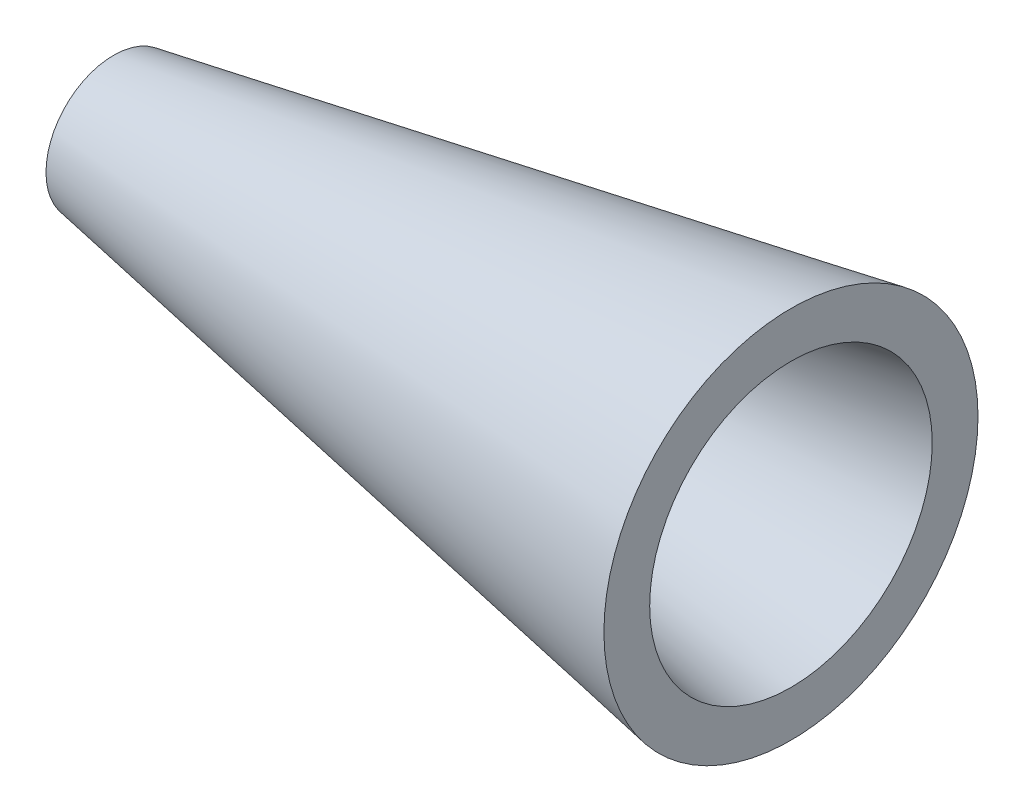
SolidWorks part; units mm, degrees
ref_plane "Front Plane" through (0, 0, 0) normal (0, 0, 1) x (1, 0, 0)
ref_plane "Top Plane" through (0, 0, 0) normal (0, 1, 0) x (1, 0, 0)
ref_plane "Right Plane" through (0, 0, 0) normal (1, 0, 0) x (0, 0, -1)
sketch "Sketch1" plane through (0, 0, 0) normal (0, 0, 1) x (1, 0, 0)
  line L0 (-20.9326, 0) -> (26.7602, 0) construction
  line L1 (-19.9997, 0) -> (-19.9997, 3)
  line L2 (-19.9997, 3) -> (10.0581, 8.3)
  line L3 (10.0581, 8.3) -> (10.0581, 0)
  line L4 (-19.9997, 3) -> (0.2267, 3) construction
  line L5 (-19.9997, 0) -> (10.0581, 0)
  dimension "D1" = 3
  dimension "D2" = 8.3
  dimension "D3" = 10
  dimension "D4" = 30.0578
revolve "Revolve1" add sketch "Sketch1" angle 360 about L0
shell "Shell1" thickness 2
